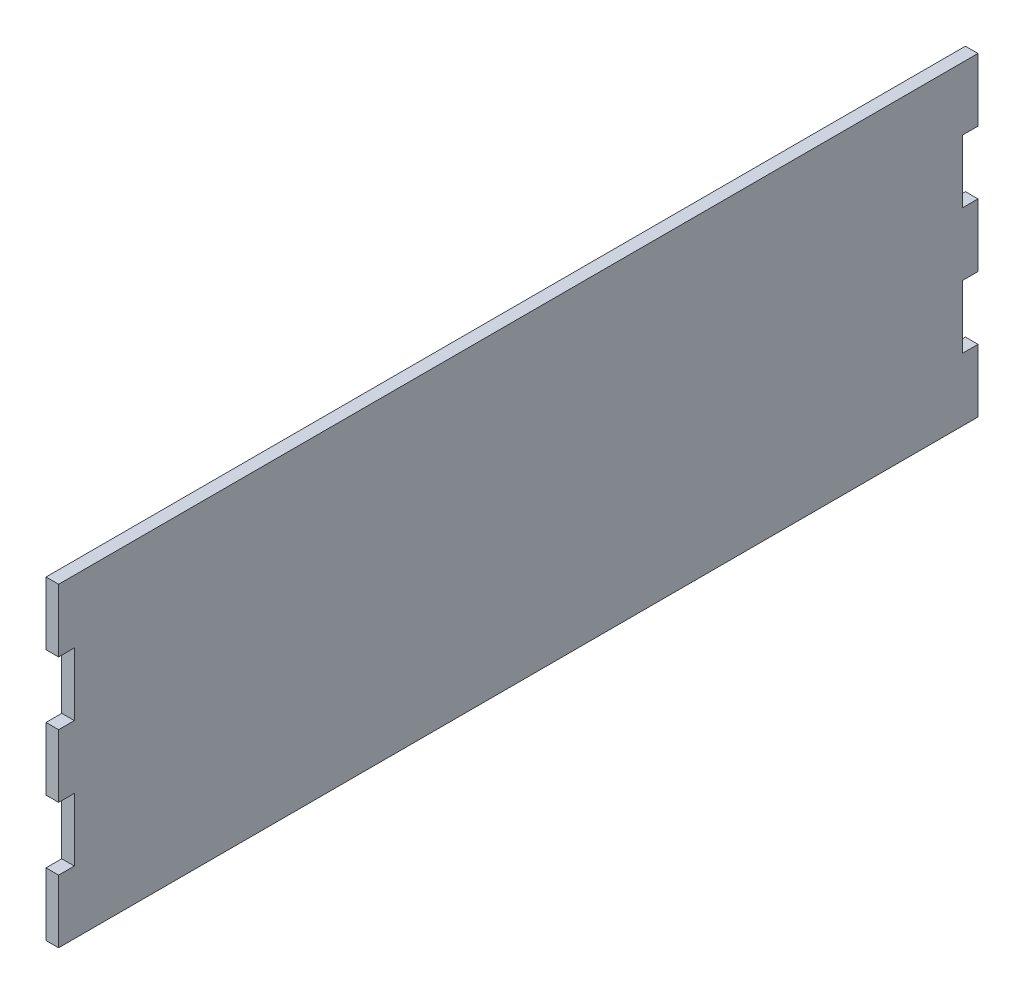
SolidWorks part; units mm, degrees
ref_plane "Front Plane" through (0, 0, 0) normal (0, 0, 1) x (1, 0, 0)
ref_plane "Top Plane" through (0, 0, 0) normal (0, 1, 0) x (1, 0, 0)
ref_plane "Right Plane" through (0, 0, 0) normal (1, 0, 0) x (0, 0, -1)
sketch "Sketch1" plane through (0, 0, 0) normal (1, 0, 0) x (0, 0, -1)
  line L0 (-1, 47.962) -> (-1, -57.038) construction
  line L1 (-147, 47.962) -> (145, 47.962)
  line L2 (-147, 47.962) -> (-147, 27.962)
  line L5 (-142, 27.962) -> (-142, 7.962)
  line L6 (-147, 27.962) -> (-142, 27.962)
  line L7 (-147, 7.962) -> (-142, 7.962)
  line L8 (-147, -12.038) -> (-142, -12.038)
  line L9 (-147, -32.038) -> (-142, -32.038)
  line L12 (-147, 7.962) -> (-147, -12.038)
  line L13 (-147, -32.038) -> (-147, -52.038)
  line L15 (-142, -12.038) -> (-142, -32.038)
  line L34 (-147, -72.038) -> (-142, -72.038) [skipped]
  line L35 (-147, -52.038) -> (-142, -52.038) [skipped]
  line L36 (-147, -52.038) -> (145, -52.038)
  line L37 (140, -12.038) -> (140, -32.038)
  line L38 (145, -32.038) -> (145, -52.038)
  line L39 (145, 7.962) -> (145, -12.038)
  line L40 (145, -32.038) -> (140, -32.038)
  line L41 (145, -12.038) -> (140, -12.038)
  line L42 (145, 7.962) -> (140, 7.962)
  line L43 (145, 27.962) -> (140, 27.962)
  line L44 (140, 27.962) -> (140, 7.962)
  line L45 (145, 47.962) -> (145, 27.962)
  point P4 (-1, -52.038)
  point P25 (0, 0)
  point P26 (0, 0)
  dimension "D1" = 146
  dimension "D3" = 5
  dimension "D4" = 20
  dimension "D6" = 20
  dimension "D7" = 20
  dimension "D8" = 20
  dimension "D9" = 20
extrude "Boss-Extrude1" add sketch "Sketch1" along normal blind 4
